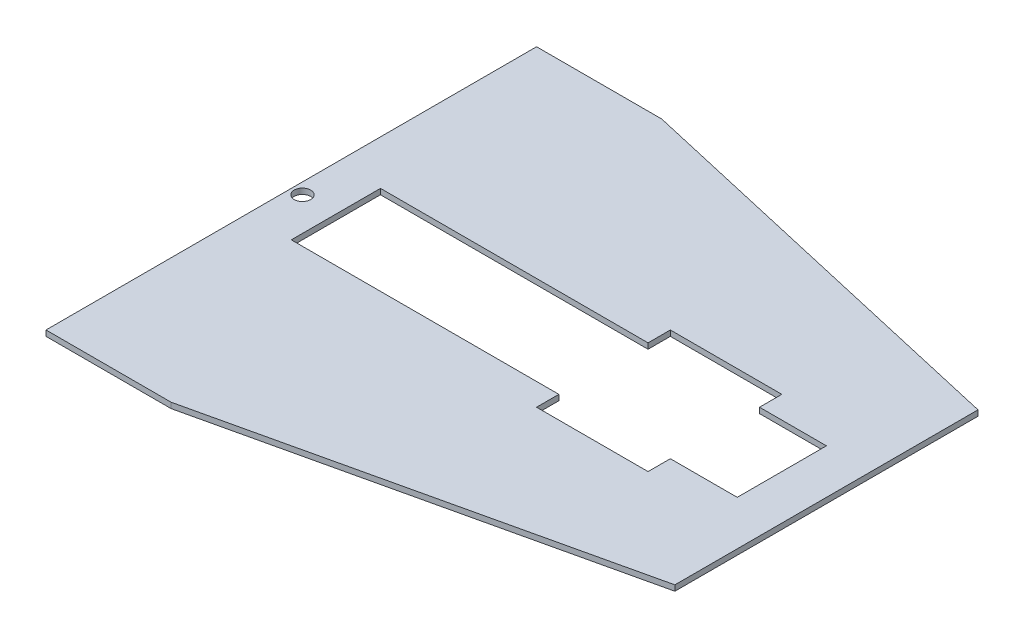
SolidWorks part; units mm, degrees
material "ASTM A36 Steel"
ref_plane "Front Plane" through (0, 0, 0) normal (0, 0, 1) x (1, 0, 0)
ref_plane "Top Plane" through (0, 0, 0) normal (0, 1, 0) x (1, 0, 0)
ref_plane "Right Plane" through (0, 0, 0) normal (1, 0, 0) x (0, 0, -1)
sketch "Sketch1" plane through (0, 0, 0) normal (0, 1, 0) x (1, 0, 0)
  line L0 (19.05, -139.7) -> (71.283, -139.7) construction
  line L1 (0, 0) -> (71.283, 0)
  line L2 (0, -279.4) -> (0, 0)
  line L3 (0, -279.4) -> (71.283, -279.4)
  line L4 (71.283, 0) -> (71.283, -279.4) construction
  line L5 (71.283, -139.7) -> (304.8, -139.7) construction
  line L6 (304.8, -53.3753) -> (304.8, -226.0247)
  line L7 (71.283, -279.4) -> (304.8, -226.0247)
  line L8 (71.283, 0) -> (304.8, -53.3753)
  line L9 (25.4, -165.1) -> (177.8, -165.1)
  line L10 (25.4, -165.1) -> (25.4, -114.3)
  line L11 (25.4, -114.3) -> (177.8, -114.3)
  line L12 (279.4, -165.1) -> (279.4, -114.3)
  line L13 (25.4, -165.1) -> (279.4, -114.3) construction
  line L14 (25.4, -114.3) -> (279.4, -165.1) construction
  line L15 (241.3, -114.3) -> (241.3, -101.6)
  line L16 (241.3, -101.6) -> (177.8, -101.6)
  line L17 (177.8, -101.6) -> (177.8, -114.3)
  line L18 (241.3, -114.3) -> (279.4, -114.3)
  line L19 (241.3, -165.1) -> (241.3, -177.8)
  line L20 (241.3, -177.8) -> (177.8, -177.8)
  line L21 (177.8, -177.8) -> (177.8, -165.1)
  line L22 (241.3, -165.1) -> (279.4, -165.1)
  circle A0 centre (6.35, -139.7) radius 4.699
  point P13 (152.4, -139.7)
  dimension "D5" = 9.398
  dimension "D6" = 6.35
  dimension "D1" = 279.4
  dimension "D2" = 304.8
  dimension "D3" = 239.5394
  dimension "D4" = 86.3247
  dimension "D7" = 139.7
  dimension "D11" = 25.4
  dimension "D12" = 50.8
  dimension "D13" = 254
  dimension "D16" = 12.7
  dimension "D17" = 63.5
  dimension "D18" = 63.5
extrude "Boss-Extrude1" add sketch "Sketch1" along normal blind 3.175
